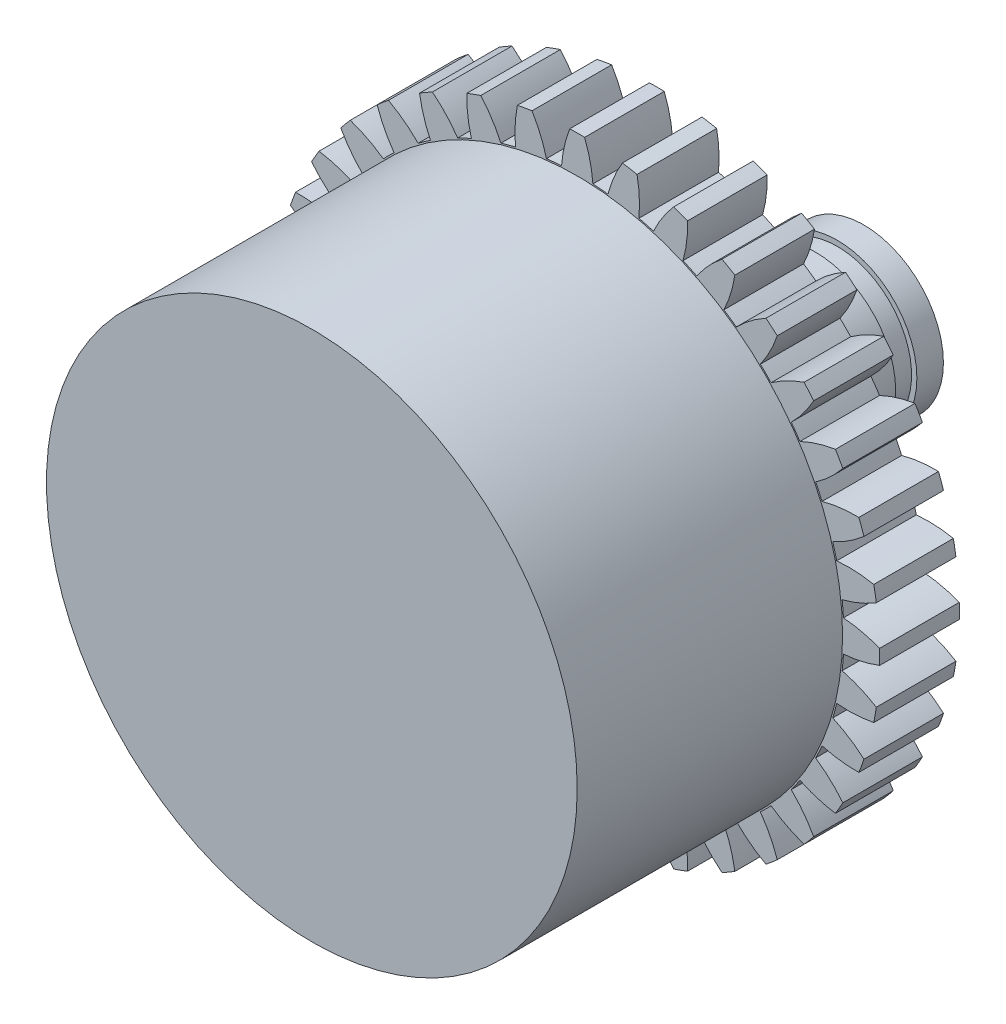
SolidWorks part; units mm, degrees
ref_plane "정면" through (0, 0, 0) normal (0, 0, 1) x (1, 0, 0)
ref_plane "윗면" through (0, 0, 0) normal (0, 1, 0) x (1, 0, 0)
ref_plane "우측면" through (0, 0, 0) normal (1, 0, 0) x (0, 0, -1)
sketch "스케치1" plane through (0, 0, 0) normal (0, 0, 1) x (1, 0, 0)
  circle A0 centre (0, 0) radius 5
  dimension "D1" = 10
extrude "보스-돌출1" add sketch "스케치1" along normal blind 5
sketch "스케치2" plane through (0, 0, 0) normal (0, 0, -1) x (-1, 0, 0)
  circle A0 centre (0, 0) radius 1.5
  dimension "D1" = 3
extrude "보스-돌출2" add sketch "스케치2" along normal blind 5.4
sketch "스케치3" plane through (0, 0, 0) normal (0, 0, -1) x (-1, 0, 0)
  circle A0 centre (0, 0) radius 2
  dimension "D1" = 4
extrude "보스-돌출3" add sketch "스케치3" along normal blind 2
sketch "스케치4" plane through (0, 0, -5.4) normal (0, 0, -1) x (-1, 0, 0)
  circle A0 centre (0, 0) radius 0.79
  dimension "D1" = 1.58
extrude "컷-돌출1" cut sketch "스케치4" against normal blind 2
sketch "스케치5" plane through (0, 0, 0) normal (0, 0, -1) x (-1, 0, 0)
  line L0 (0, 0) -> (0, 5.7) construction
  line L1 (0, 0) -> (-0.2355, 5.3949) construction
  line L2 (-0.2355, 5.3949) -> (-0.1399, 5.6983) construction
  line L3 (-0.2355, 5.3949) -> (-1.0666, 0.1696) construction
  circle A0 centre (0, 0) radius 5.4 construction
  circle A1 centre (0, 0) radius 5.7 construction
  circle A2 centre (0, 0) radius 5.025 construction
  circle A3 centre (0, 0) radius 1.08 construction
  arc A4 (-0.2958, 5.0163) -> (-0.1399, 5.6983) centre (2.074, 4.8335) cw
  arc A5 (0.2958, 5.0163) -> (0.1399, 5.6983) centre (-2.074, 4.8335) ccw
  arc A6 (-0.1399, 5.6983) -> (0.1399, 5.6983) centre (0, 0) cw
  arc A7 (1.1623, 4.8887) -> (1.1272, 5.5874) centre (-1.2031, 5.1202) ccw
  arc A8 (0.8517, 5.636) -> (1.1272, 5.5874) centre (0, 0) cw
  arc A9 (0.5798, 4.9914) -> (0.8517, 5.636) centre (2.8818, 4.3999) cw
  arc A10 (1.9936, 4.6126) -> (2.0804, 5.3068) centre (-0.2957, 5.2513) ccw
  arc A11 (1.8175, 5.4025) -> (2.0804, 5.3068) centre (0, 0) cw
  arc A12 (1.4378, 4.8149) -> (1.8175, 5.4025) centre (3.602, 3.8326) cw
  arc A13 (2.7643, 4.1964) -> (2.9703, 4.8649) centre (0.6206, 5.2229) ccw
  arc A14 (2.728, 5.0048) -> (2.9703, 4.8649) centre (0, 0) cw
  arc A15 (2.252, 4.4921) -> (2.728, 5.0048) centre (4.2128, 3.1489) cw
  arc A16 (3.451, 3.6526) -> (3.7699, 4.2752) centre (1.5181, 5.0358) ccw
  arc A17 (3.5556, 4.455) -> (3.7699, 4.2752) centre (0, 0) cw
  arc A18 (2.9978, 4.0328) -> (3.5556, 4.455) centre (4.6956, 2.3695) cw
  arc A19 (4.0328, 2.9978) -> (4.455, 3.5556) centre (2.3695, 4.6956) ccw
  arc A20 (4.2752, 3.7699) -> (4.455, 3.5556) centre (0, 0) cw
  arc A21 (3.6526, 3.451) -> (4.2752, 3.7699) centre (5.0358, 1.5181) cw
  arc A22 (4.4921, 2.252) -> (5.0048, 2.728) centre (3.1489, 4.2128) ccw
  arc A23 (4.8649, 2.9703) -> (5.0048, 2.728) centre (0, 0) cw
  arc A24 (4.1964, 2.7643) -> (4.8649, 2.9703) centre (5.2229, 0.6206) cw
  arc A25 (4.8149, 1.4378) -> (5.4025, 1.8175) centre (3.8326, 3.602) ccw
  arc A26 (5.3068, 2.0804) -> (5.4025, 1.8175) centre (0, 0) cw
  arc A27 (4.6126, 1.9936) -> (5.3068, 2.0804) centre (5.2513, -0.2957) cw
  arc A28 (4.9914, 0.5798) -> (5.636, 0.8517) centre (4.3999, 2.8818) ccw
  arc A29 (5.5874, 1.1272) -> (5.636, 0.8517) centre (0, 0) cw
  arc A30 (4.8887, 1.1623) -> (5.5874, 1.1272) centre (5.1202, -1.2031) cw
  arc A31 (5.0163, -0.2958) -> (5.6983, -0.1399) centre (4.8335, 2.074) ccw
  arc A32 (5.6983, 0.1399) -> (5.6983, -0.1399) centre (0, 0) cw
  arc A33 (5.0163, 0.2958) -> (5.6983, 0.1399) centre (4.8335, -2.074) cw
  arc A34 (4.8887, -1.1623) -> (5.5874, -1.1272) centre (5.1202, 1.2031) ccw
  arc A35 (5.636, -0.8517) -> (5.5874, -1.1272) centre (0, 0) cw
  arc A36 (4.9914, -0.5798) -> (5.636, -0.8517) centre (4.3999, -2.8818) cw
  arc A37 (4.6126, -1.9936) -> (5.3068, -2.0804) centre (5.2513, 0.2957) ccw
  arc A38 (5.4025, -1.8175) -> (5.3068, -2.0804) centre (0, 0) cw
  arc A39 (4.8149, -1.4378) -> (5.4025, -1.8175) centre (3.8326, -3.602) cw
  arc A40 (4.1964, -2.7643) -> (4.8649, -2.9703) centre (5.2229, -0.6206) ccw
  arc A41 (5.0048, -2.728) -> (4.8649, -2.9703) centre (0, 0) cw
  arc A42 (4.4921, -2.252) -> (5.0048, -2.728) centre (3.1489, -4.2128) cw
  arc A43 (3.6526, -3.451) -> (4.2752, -3.7699) centre (5.0358, -1.5181) ccw
  arc A44 (4.455, -3.5556) -> (4.2752, -3.7699) centre (0, 0) cw
  arc A45 (4.0328, -2.9978) -> (4.455, -3.5556) centre (2.3695, -4.6956) cw
  arc A46 (2.9978, -4.0328) -> (3.5556, -4.455) centre (4.6956, -2.3695) ccw
  arc A47 (3.7699, -4.2752) -> (3.5556, -4.455) centre (0, 0) cw
  arc A48 (3.451, -3.6526) -> (3.7699, -4.2752) centre (1.5181, -5.0358) cw
  arc A49 (2.252, -4.4921) -> (2.728, -5.0048) centre (4.2128, -3.1489) ccw
  arc A50 (2.9703, -4.8649) -> (2.728, -5.0048) centre (0, 0) cw
  arc A51 (2.7643, -4.1964) -> (2.9703, -4.8649) centre (0.6206, -5.2229) cw
  arc A52 (1.4378, -4.8149) -> (1.8175, -5.4025) centre (3.602, -3.8326) ccw
  arc A53 (2.0804, -5.3068) -> (1.8175, -5.4025) centre (0, 0) cw
  arc A54 (1.9936, -4.6126) -> (2.0804, -5.3068) centre (-0.2957, -5.2513) cw
  arc A55 (0.5798, -4.9914) -> (0.8517, -5.636) centre (2.8818, -4.3999) ccw
  arc A56 (1.1272, -5.5874) -> (0.8517, -5.636) centre (0, 0) cw
  arc A57 (1.1623, -4.8887) -> (1.1272, -5.5874) centre (-1.2031, -5.1202) cw
  arc A58 (-0.2958, -5.0163) -> (-0.1399, -5.6983) centre (2.074, -4.8335) ccw
  arc A59 (0.1399, -5.6983) -> (-0.1399, -5.6983) centre (0, 0) cw
  arc A60 (0.2958, -5.0163) -> (0.1399, -5.6983) centre (-2.074, -4.8335) cw
  arc A61 (-1.1623, -4.8887) -> (-1.1272, -5.5874) centre (1.2031, -5.1202) ccw
  arc A62 (-0.8517, -5.636) -> (-1.1272, -5.5874) centre (0, 0) cw
  arc A63 (-0.5798, -4.9914) -> (-0.8517, -5.636) centre (-2.8818, -4.3999) cw
  arc A64 (-1.9936, -4.6126) -> (-2.0804, -5.3068) centre (0.2957, -5.2513) ccw
  arc A65 (-1.8175, -5.4025) -> (-2.0804, -5.3068) centre (0, 0) cw
  arc A66 (-1.4378, -4.8149) -> (-1.8175, -5.4025) centre (-3.602, -3.8326) cw
  arc A67 (-2.7643, -4.1964) -> (-2.9703, -4.8649) centre (-0.6206, -5.2229) ccw
  arc A68 (-2.728, -5.0048) -> (-2.9703, -4.8649) centre (0, 0) cw
  arc A69 (-2.252, -4.4921) -> (-2.728, -5.0048) centre (-4.2128, -3.1489) cw
  arc A70 (-3.451, -3.6526) -> (-3.7699, -4.2752) centre (-1.5181, -5.0358) ccw
  arc A71 (-3.5556, -4.455) -> (-3.7699, -4.2752) centre (0, 0) cw
  arc A72 (-2.9978, -4.0328) -> (-3.5556, -4.455) centre (-4.6956, -2.3695) cw
  arc A73 (-4.0328, -2.9978) -> (-4.455, -3.5556) centre (-2.3695, -4.6956) ccw
  arc A74 (-4.2752, -3.7699) -> (-4.455, -3.5556) centre (0, 0) cw
  arc A75 (-3.6526, -3.451) -> (-4.2752, -3.7699) centre (-5.0358, -1.5181) cw
  arc A76 (-4.4921, -2.252) -> (-5.0048, -2.728) centre (-3.1489, -4.2128) ccw
  arc A77 (-4.8649, -2.9703) -> (-5.0048, -2.728) centre (0, 0) cw
  arc A78 (-4.1964, -2.7643) -> (-4.8649, -2.9703) centre (-5.2229, -0.6206) cw
  arc A79 (-4.8149, -1.4378) -> (-5.4025, -1.8175) centre (-3.8326, -3.602) ccw
  arc A80 (-5.3068, -2.0804) -> (-5.4025, -1.8175) centre (0, 0) cw
  arc A81 (-4.6126, -1.9936) -> (-5.3068, -2.0804) centre (-5.2513, 0.2957) cw
  arc A82 (-4.9914, -0.5798) -> (-5.636, -0.8517) centre (-4.3999, -2.8818) ccw
  arc A83 (-5.5874, -1.1272) -> (-5.636, -0.8517) centre (0, 0) cw
  arc A84 (-4.8887, -1.1623) -> (-5.5874, -1.1272) centre (-5.1202, 1.2031) cw
  arc A85 (-5.0163, 0.2958) -> (-5.6983, 0.1399) centre (-4.8335, -2.074) ccw
  arc A86 (-5.6983, -0.1399) -> (-5.6983, 0.1399) centre (0, 0) cw
  arc A87 (-5.0163, -0.2958) -> (-5.6983, -0.1399) centre (-4.8335, 2.074) cw
  arc A88 (-4.8887, 1.1623) -> (-5.5874, 1.1272) centre (-5.1202, -1.2031) ccw
  arc A89 (-5.636, 0.8517) -> (-5.5874, 1.1272) centre (0, 0) cw
  arc A90 (-4.9914, 0.5798) -> (-5.636, 0.8517) centre (-4.3999, 2.8818) cw
  arc A91 (-4.6126, 1.9936) -> (-5.3068, 2.0804) centre (-5.2513, -0.2957) ccw
  arc A92 (-5.4025, 1.8175) -> (-5.3068, 2.0804) centre (0, 0) cw
  arc A93 (-4.8149, 1.4378) -> (-5.4025, 1.8175) centre (-3.8326, 3.602) cw
  arc A94 (-4.1964, 2.7643) -> (-4.8649, 2.9703) centre (-5.2229, 0.6206) ccw
  arc A95 (-5.0048, 2.728) -> (-4.8649, 2.9703) centre (0, 0) cw
  arc A96 (-4.4921, 2.252) -> (-5.0048, 2.728) centre (-3.1489, 4.2128) cw
  arc A97 (-3.6526, 3.451) -> (-4.2752, 3.7699) centre (-5.0358, 1.5181) ccw
  arc A98 (-4.455, 3.5556) -> (-4.2752, 3.7699) centre (0, 0) cw
  arc A99 (-4.0328, 2.9978) -> (-4.455, 3.5556) centre (-2.3695, 4.6956) cw
  arc A100 (-2.9978, 4.0328) -> (-3.5556, 4.455) centre (-4.6956, 2.3695) ccw
  arc A101 (-3.7699, 4.2752) -> (-3.5556, 4.455) centre (0, 0) cw
  arc A102 (-3.451, 3.6526) -> (-3.7699, 4.2752) centre (-1.5181, 5.0358) cw
  arc A103 (-2.252, 4.4921) -> (-2.728, 5.0048) centre (-4.2128, 3.1489) ccw
  arc A104 (-2.9703, 4.8649) -> (-2.728, 5.0048) centre (0, 0) cw
  arc A105 (-2.7643, 4.1964) -> (-2.9703, 4.8649) centre (-0.6206, 5.2229) cw
  arc A106 (-1.4378, 4.8149) -> (-1.8175, 5.4025) centre (-3.602, 3.8326) ccw
  arc A107 (-2.0804, 5.3068) -> (-1.8175, 5.4025) centre (0, 0) cw
  arc A108 (-1.9936, 4.6126) -> (-2.0804, 5.3068) centre (0.2957, 5.2513) cw
  arc A109 (-0.5798, 4.9914) -> (-0.8517, 5.636) centre (-2.8818, 4.3999) ccw
  arc A110 (-1.1272, 5.5874) -> (-0.8517, 5.636) centre (0, 0) cw
  arc A111 (-1.1623, 4.8887) -> (-1.1272, 5.5874) centre (1.2031, 5.1202) cw
  arc A112 (0.2958, 5.0163) -> (0.5798, 4.9914) centre (0, 0) cw
  arc A113 (1.1623, 4.8887) -> (1.4378, 4.8149) centre (0, 0) cw
  arc A114 (1.9936, 4.6126) -> (2.252, 4.4921) centre (0, 0) cw
  arc A115 (2.7643, 4.1964) -> (2.9978, 4.0328) centre (0, 0) cw
  arc A116 (3.451, 3.6526) -> (3.6526, 3.451) centre (0, 0) cw
  arc A117 (4.0328, 2.9978) -> (4.1964, 2.7643) centre (0, 0) cw
  arc A118 (4.4921, 2.252) -> (4.6126, 1.9936) centre (0, 0) cw
  arc A119 (4.8149, 1.4378) -> (4.8887, 1.1623) centre (0, 0) cw
  arc A120 (4.9914, 0.5798) -> (5.0163, 0.2958) centre (0, 0) cw
  arc A121 (5.0163, -0.2958) -> (4.9914, -0.5798) centre (0, 0) cw
  arc A122 (4.8887, -1.1623) -> (4.8149, -1.4378) centre (0, 0) cw
  arc A123 (4.6126, -1.9936) -> (4.4921, -2.252) centre (0, 0) cw
  arc A124 (4.1964, -2.7643) -> (4.0328, -2.9978) centre (0, 0) cw
  arc A125 (3.6526, -3.451) -> (3.451, -3.6526) centre (0, 0) cw
  arc A126 (2.9978, -4.0328) -> (2.7643, -4.1964) centre (0, 0) cw
  arc A127 (2.252, -4.4921) -> (1.9936, -4.6126) centre (0, 0) cw
  arc A128 (1.4378, -4.8149) -> (1.1623, -4.8887) centre (0, 0) cw
  arc A129 (0.5798, -4.9914) -> (0.2958, -5.0163) centre (0, 0) cw
  arc A130 (-0.2958, -5.0163) -> (-0.5798, -4.9914) centre (0, 0) cw
  arc A131 (-1.1623, -4.8887) -> (-1.4378, -4.8149) centre (0, 0) cw
  arc A132 (-1.9936, -4.6126) -> (-2.252, -4.4921) centre (0, 0) cw
  arc A133 (-2.7643, -4.1964) -> (-2.9978, -4.0328) centre (0, 0) cw
  arc A134 (-3.451, -3.6526) -> (-3.6526, -3.451) centre (0, 0) cw
  arc A135 (-4.0328, -2.9978) -> (-4.1964, -2.7643) centre (0, 0) cw
  arc A136 (-4.4921, -2.252) -> (-4.6126, -1.9936) centre (0, 0) cw
  arc A137 (-4.8149, -1.4378) -> (-4.8887, -1.1623) centre (0, 0) cw
  arc A138 (-4.9914, -0.5798) -> (-5.0163, -0.2958) centre (0, 0) cw
  arc A139 (-5.0163, 0.2958) -> (-4.9914, 0.5798) centre (0, 0) cw
  arc A140 (-4.8887, 1.1623) -> (-4.8149, 1.4378) centre (0, 0) cw
  arc A141 (-4.6126, 1.9936) -> (-4.4921, 2.252) centre (0, 0) cw
  arc A142 (-4.1964, 2.7643) -> (-4.0328, 2.9978) centre (0, 0) cw
  arc A143 (-3.6526, 3.451) -> (-3.451, 3.6526) centre (0, 0) cw
  arc A144 (-2.9978, 4.0328) -> (-2.7643, 4.1964) centre (0, 0) cw
  arc A145 (-2.252, 4.4921) -> (-1.9936, 4.6126) centre (0, 0) cw
  arc A146 (-1.4378, 4.8149) -> (-1.1623, 4.8887) centre (0, 0) cw
  arc A147 (-0.5798, 4.9914) -> (-0.2958, 5.0163) centre (0, 0) cw
  point P12 (-0.2958, 5.0163)
  point P230 (0, 0)
  point P302 (0, 0)
  dimension "D1" = 10.8
  dimension "D2" = 0.375
  dimension "D3" = 0.3
  dimension "D6" = 2.16
  dimension "D4" = 2.5
  dimension "D5" = 20
  dimension "D7" = 36
  dimension "D8" = 36
extrude "보스-돌출4" add sketch "스케치5" along normal blind 1.5
sketch "스케치7" plane through (0, 0, -1.5) normal (0, 0, -1) x (-1, 0, 0)
  circle A0 centre (0, 0) radius 1.4
  circle A1 centre (0, 0) radius 2
  dimension "D1" = 4
  dimension "D2" = 2.8
extrude "컷-돌출3" cut sketch "스케치7" along normal blind 0.4 from offset 3
